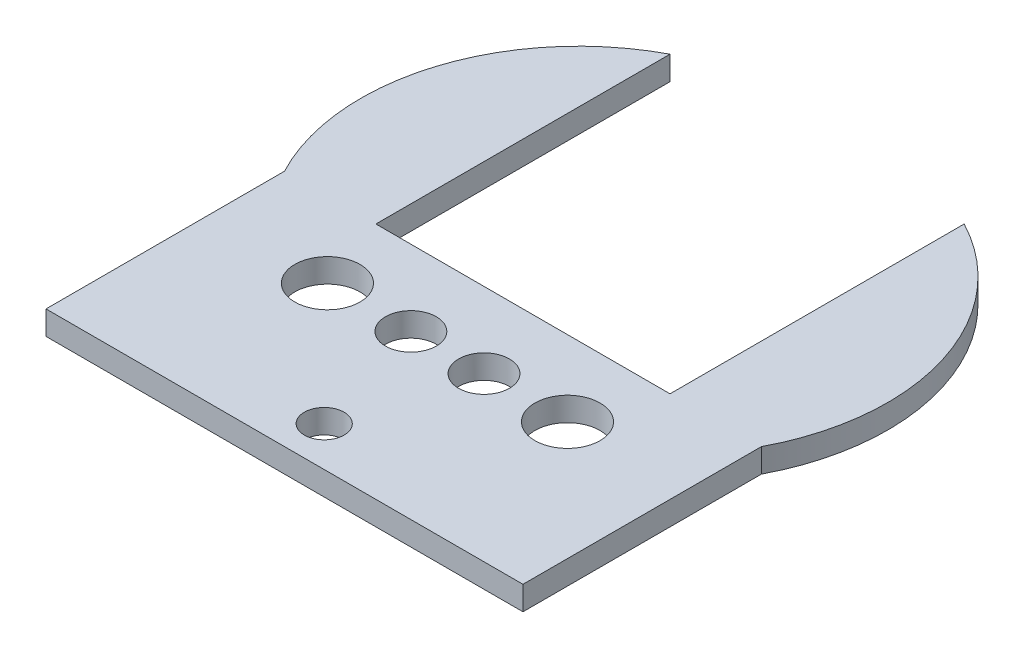
SolidWorks part; units mm, degrees
ref_plane "Front Plane" through (0, 0, 0) normal (0, 0, 1) x (1, 0, 0)
ref_plane "Top Plane" through (0, 0, 0) normal (0, 1, 0) x (1, 0, 0)
ref_plane "Right Plane" through (0, 0, 0) normal (1, 0, 0) x (0, 0, -1)
sketch "Sketch1" plane through (0, 0, 0) normal (0, 1, 0) x (1, 0, 0)
  line L0 (-19.8017, 0) -> (17.1983, 0)
  line L1 (-19.8017, 0) -> (-19.8017, 37)
  line L2 (17.1983, 0) -> (17.1983, 37)
  line L3 (-19.8017, 0) -> (-31.3017, 0) construction
  line L4 (17.1983, 0) -> (5.5712, 0) construction
  line L8 (17.1983, 0) -> (28.6983, 0) construction
  line L9 (-31.3017, 0) -> (-31.3017, -30)
  line L10 (-31.3017, -30) -> (28.6983, -30)
  line L11 (28.6983, -30) -> (28.6983, 0)
  arc A4 (-19.8017, 37) -> (-31.3017, 0) centre (-7.0517, 12.75) ccw
  arc A5 (17.1983, 37) -> (28.6983, 0) centre (4.4483, 12.75) cw
  dimension "D1" = 37
  dimension "D2" = 30
extrude "Boss-Extrude1" add sketch "Sketch1" along normal blind 3
sketch "Sketch2" plane through (0, 3, 0) normal (0, 1, 0) x (1, 0, 0)
  line L0 (-1.3017, -30) -> (-1.3017, -20) construction
  line L2 (-31.3017, -30) -> (28.6983, -30) construction
  circle A1 centre (-1.3017, -25) radius 2.5
  circle A2 centre (-1.3017, -25) radius 2.4697 construction
  dimension "D1" = 0
extrude "Cut-Extrude1" cut sketch "Sketch2" against normal blind 20
sketch "Sketch3" plane through (0, 0, 0) normal (0, -1, 0) x (1, 0, 0)
  line L0 (28.6983, 30) -> (28.6983, 0) construction
  line L1 (16.2983, 7) -> (11.2983, 7)
  line L2 (16.2983, 7) -> (16.2983, 12)
  line L3 (16.2983, 12) -> (11.2983, 12)
  line L4 (11.2983, 7) -> (11.2983, 12)
  line L5 (17.1983, 0) -> (-19.8017, 0) construction
  line L6 (-1.3017, 0) -> (-1.3017, 45) construction
  line L7 (13.7983, 7) -> (13.7983, 12) construction
  line L8 (-13.9017, 7) -> (-13.9017, 12)
  line L9 (-18.9017, 12) -> (-13.9017, 12)
  line L10 (-18.9017, 7) -> (-18.9017, 12)
  line L11 (-18.9017, 7) -> (-13.9017, 7)
  dimension "D1" = 15.1
  dimension "D2" = 7
  dimension "D3" = 5
  dimension "D4" = 30
extrude "Cut-Extrude2" cut sketch "Sketch3" against normal blind 10
sketch "Sketch4" plane through (0, 0, 0) normal (0, -1, 0) x (1, 0, 0)
  line L0 (13.7983, 7) -> (13.7983, 12) construction
  line L1 (11.2983, 7) -> (16.2983, 7) construction
  line L2 (16.2983, 12) -> (11.2983, 12) construction
  line L3 (16.2983, 9.5) -> (11.2983, 9.5) construction
  line L4 (16.2983, 7) -> (16.2983, 12) construction
  line L5 (11.2983, 12) -> (11.2983, 7) construction
  line L6 (-1.3017, 0) -> (-1.3017, 30) construction
  line L7 (17.1983, 0) -> (-19.8017, 0) construction
  line L8 (-31.3017, 30) -> (28.6983, 30) construction
  line L9 (28.6983, 30) -> (28.6983, 0) construction
  circle A0 centre (13.7983, 9.5) radius 4.1
  circle A1 centre (-16.4017, 9.5) radius 4.1
  dimension "D2" = 8.2
  dimension "D1" = 30
extrude "Cut-Extrude3" cut sketch "Sketch4" against normal blind 10
sketch "Sketch5" plane through (0, 3, 0) normal (0, 1, 0) x (1, 0, 0)
  line L0 (-1.3017, 0) -> (-1.3017, -38.9108) construction
  line L1 (17.1983, 0) -> (-19.8017, 0) construction
  circle A1 centre (-5.9017, -9.5) radius 3.2
  circle A2 centre (3.2983, -9.5) radius 3.2
  dimension "D1" = 6.4
  dimension "D2" = 4.6
  dimension "D3" = 0
extrude "Cut-Extrude4" cut sketch "Sketch5" against normal blind 10
